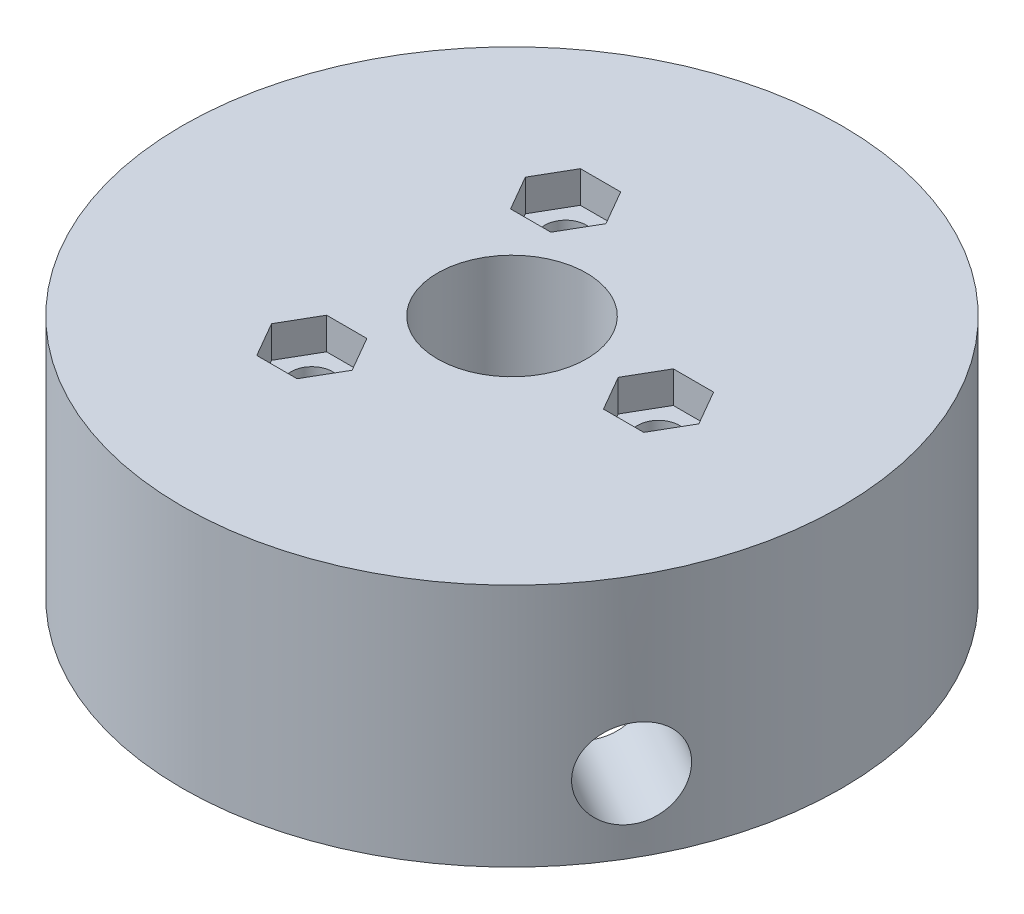
SolidWorks part; units mm, degrees
other "Printed Wheel Rim"
other "Printed Wheel Rim Left"
ref_plane "Front Plane" through (0, 0, 0) normal (0, 0, 1) x (1, 0, 0)
ref_plane "Top Plane" through (0, 0, 0) normal (0, 1, 0) x (1, 0, 0)
ref_plane "Right Plane" through (0, 0, 0) normal (1, 0, 0) x (0, 0, -1)
sketch3d "Tyre seat blank sketch datum points"
  point P0 (-19.0092, -283, -53.2449)
  point P1 (-9.0092, -283, -53.2449)
  point P2 (-19.0092, -283, -63.2449)
ref_plane "Tyre seat blank sketch plane" through (0, -283, 0) normal (0, 1, 0) x (1, 0, 0)
sketch "Tyre seat blank sketch" plane through (0, -283, 0) normal (0, 1, 0) x (1, 0, 0)
  circle A0 centre (-19.0092, 53.2449) radius 27
extrude "Tyre seat blank" add sketch "Tyre seat blank sketch" along normal blind 20 separate body
sketch3d "Axle clearance sketch datum points"
  point P0 (-19.0092, -283.1, -53.2449)
  point P1 (-9.0092, -283.1, -53.2449)
  point P2 (-19.0092, -283.1, -63.2449)
ref_plane "Axle clearance sketch plane" through (0, -283.1, 0) normal (0, 1, 0) x (1, 0, 0)
sketch "Axle clearance sketch" plane through (0, -283.1, 0) normal (0, 1, 0) x (1, 0, 0)
  circle A0 centre (-19.0092, 53.2449) radius 6.1
extrude "Axle clearance" cut sketch "Axle clearance sketch" along normal blind 20.2
sketch3d "Hub neck socket sketch datum points"
  point P0 (-19.0092, -273.3, -53.2449)
  point P1 (-9.0092, -273.3, -53.2449)
  point P2 (-19.0092, -273.3, -63.2449)
ref_plane "Hub neck socket sketch plane" through (0, -273.3, 0) normal (0, 1, 0) x (1, 0, 0)
sketch "Hub neck socket sketch" plane through (0, -273.3, 0) normal (0, 1, 0) x (1, 0, 0)
  circle A0 centre (-19.0092, 53.2449) radius 9.2
extrude "Hub neck socket" cut sketch "Hub neck socket sketch" along normal blind 10.5
sketch3d "Hub flange socket sketch datum points"
  point P0 (-19.0092, -266.3, -53.2449)
  point P1 (-9.0092, -266.3, -53.2449)
  point P2 (-19.0092, -266.3, -63.2449)
ref_plane "Hub flange socket sketch plane" through (0, -266.3, 0) normal (0, 1, 0) x (1, 0, 0)
sketch "Hub flange socket sketch" plane through (0, -266.3, 0) normal (0, 1, 0) x (1, 0, 0)
  circle A0 centre (-19.0092, 53.2449) radius 18.2
extrude "Hub flange socket" cut sketch "Hub flange socket sketch" along normal blind 3.5
sketch3d "Rim bolt pattern sketch datum points"
  point P0 (-19.0092, -283.1, -53.2449)
  point P1 (-9.0092, -283.1, -53.2449)
  point P2 (-19.0092, -283.1, -63.2449)
ref_plane "Rim bolt pattern sketch plane" through (0, -283.1, 0) normal (0, 1, 0) x (1, 0, 0)
sketch "Rim bolt pattern sketch" plane through (0, -283.1, 0) normal (0, 1, 0) x (1, 0, 0)
  circle A0 centre (-7.0092, 53.2449) radius 1.7
  circle A1 centre (-25.0092, 42.8526) radius 1.7
  circle A2 centre (-25.0092, 63.6372) radius 1.7
extrude "Rim bolt pattern" cut sketch "Rim bolt pattern sketch" along normal blind 20.2
sketch3d "Rim nut pockets sketch datum points"
  point P0 (-19.0092, -283.1, -53.2449)
  point P1 (-9.0092, -283.1, -53.2449)
  point P2 (-19.0092, -283.1, -63.2449)
ref_plane "Rim nut pockets sketch plane" through (0, -283.1, 0) normal (0, 1, 0) x (1, 0, 0)
sketch "Rim nut pockets sketch" plane through (0, -283.1, 0) normal (0, 1, 0) x (1, 0, 0)
  line L0 (-3.7092, 53.2449) -> (-5.3592, 56.1028)
  line L1 (-5.3592, 56.1028) -> (-8.6592, 56.1028)
  line L2 (-8.6592, 56.1028) -> (-10.3092, 53.2449)
  line L3 (-10.3092, 53.2449) -> (-8.6592, 50.387)
  line L4 (-8.6592, 50.387) -> (-5.3592, 50.387)
  line L5 (-5.3592, 50.387) -> (-3.7092, 53.2449)
  line L6 (-21.7092, 42.8526) -> (-23.3592, 45.7105)
  line L7 (-23.3592, 45.7105) -> (-26.6592, 45.7105)
  line L8 (-26.6592, 45.7105) -> (-28.3092, 42.8526)
  line L9 (-28.3092, 42.8526) -> (-26.6592, 39.9947)
  line L10 (-26.6592, 39.9947) -> (-23.3592, 39.9947)
  line L11 (-23.3592, 39.9947) -> (-21.7092, 42.8526)
  line L12 (-21.7092, 63.6372) -> (-23.3592, 66.4951)
  line L13 (-23.3592, 66.4951) -> (-26.6592, 66.4951)
  line L14 (-26.6592, 66.4951) -> (-28.3092, 63.6372)
  line L15 (-28.3092, 63.6372) -> (-26.6592, 60.7793)
  line L16 (-26.6592, 60.7793) -> (-23.3592, 60.7793)
  line L17 (-23.3592, 60.7793) -> (-21.7092, 63.6372)
  circle A0 centre (-7.0092, 53.2449) radius 3.3 construction
  circle A1 centre (-25.0092, 42.8526) radius 3.3 construction
  circle A2 centre (-25.0092, 63.6372) radius 3.3 construction
extrude "Rim nut pockets" cut sketch "Rim nut pockets sketch" along normal blind 2.7
sketch3d "Hub pin service window sketch datum points"
  point P0 (-43.2579, -269, -67.2449)
  point P1 (-38.2579, -269, -75.9051)
  point P2 (-43.2579, -259, -67.2449)
ref_plane "Hub pin service window sketch plane" through (-61.5613, 0, -35.5424) normal (0.866, 0, 0.5) x (0.5, 0, -0.866)
sketch "Hub pin service window sketch" plane through (-61.5613, 0, -35.5424) normal (0.866, 0, 0.5) x (0.5, 0, -0.866)
  circle A0 centre (36.6068, -269) radius 3.6
extrude "Hub pin service window" cut sketch "Hub pin service window sketch" along normal blind 56
sketch3d "Mirror1 profile datum points"
  point P0 (0, 0, 0)
  point P1 (10, 0, 0)
  point P2 (0, 0, 10)
ref_plane "Mirror1 profile plane" through (0, 0, 0) normal (0, -1, 0) x (-1, 0, 0)
mirror "Mirror1" about plane through (0, 0, 0) normal (0, -1, 0) of bodies 107
delete or keep bodies "Remove1" type delete bodies bodies 107
